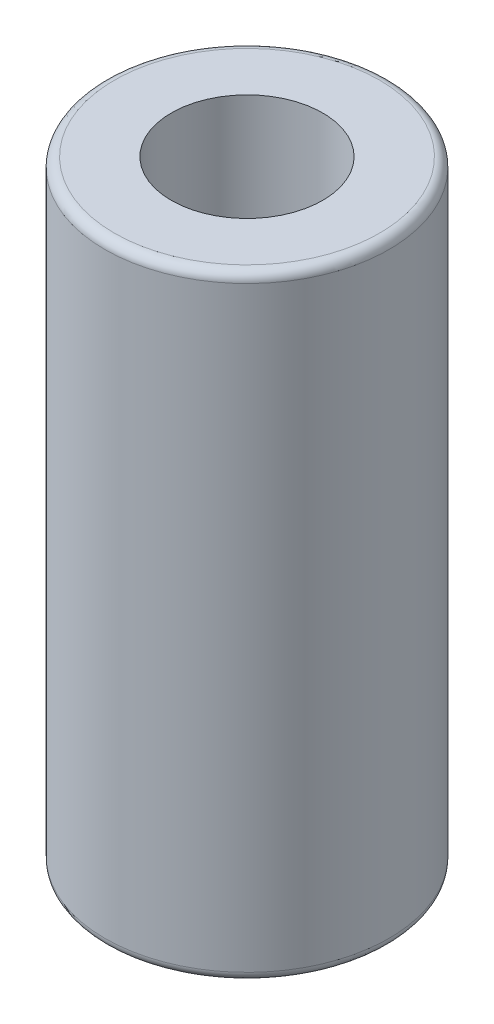
SolidWorks part; units mm, degrees
ref_plane "Front Plane" through (0, 0, 0) normal (0, 0, 1) x (1, 0, 0)
ref_plane "Top Plane" through (0, 0, 0) normal (0, 1, 0) x (1, 0, 0)
ref_plane "Right Plane" through (0, 0, 0) normal (1, 0, 0) x (0, 0, -1)
sketch "Sketch1" plane through (0, 0, 0) normal (0, 1, 0) x (1, 0, 0)
  circle A0 centre (0, 0) radius 3
  dimension "D1" = 6
extrude "Boss-Extrude1" add sketch "Sketch1" along normal blind 13
sketch "Sketch2" plane through (0, 13, 0) normal (0, 1, 0) x (1, 0, 0)
  circle A0 centre (0, 0) radius 1.6
  dimension "D1" = 3.2
extrude "Cut-Extrude1" cut sketch "Sketch2" against normal through all
fillet "Fillet1" radius 0.2 2 edges at (0, 0, 3) (0, 13, 3)
